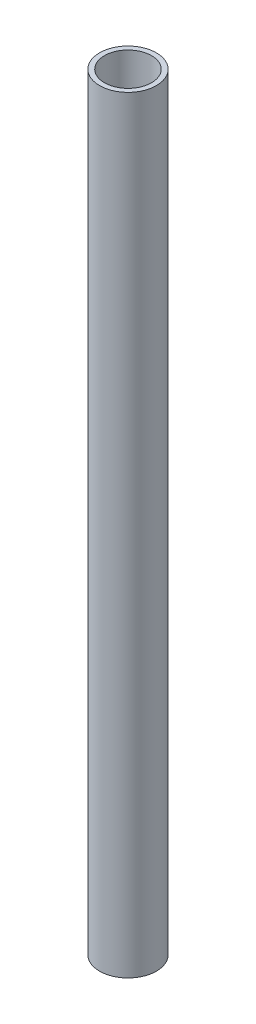
SolidWorks part; units mm, degrees
ref_plane "Płaszczyzna przednia" through (0, 0, 0) normal (0, 0, 1) x (1, 0, 0)
ref_plane "Płaszczyzna górna" through (0, 0, 0) normal (0, 1, 0) x (1, 0, 0)
ref_plane "Płaszczyzna prawa" through (0, 0, 0) normal (1, 0, 0) x (0, 0, -1)
sketch3d "Szkic 3D1"
  line L0 (0, 0, 0) -> (0, 1200, 0)
  dimension "D1" = 1200
other "Rura grubościenna x; wzmocniona, s80 PIPE XS 3 SCH 80(1)"
ref_plane "Płaszczyzna1" through (0, 0, 0) normal (0, 1, 0) x (1, 0, 0)
sketch "Sketch12" plane through (0, 0, 0) normal (0, 1, 0) x (1, 0, 0)
  circle A0 centre (0, 0) radius 36.83
  circle A1 centre (0, 0) radius 44.45
  point P3 (0, 0)
  dimension "In_dia" = 73.66
  dimension "Out_dia" = 88.9
